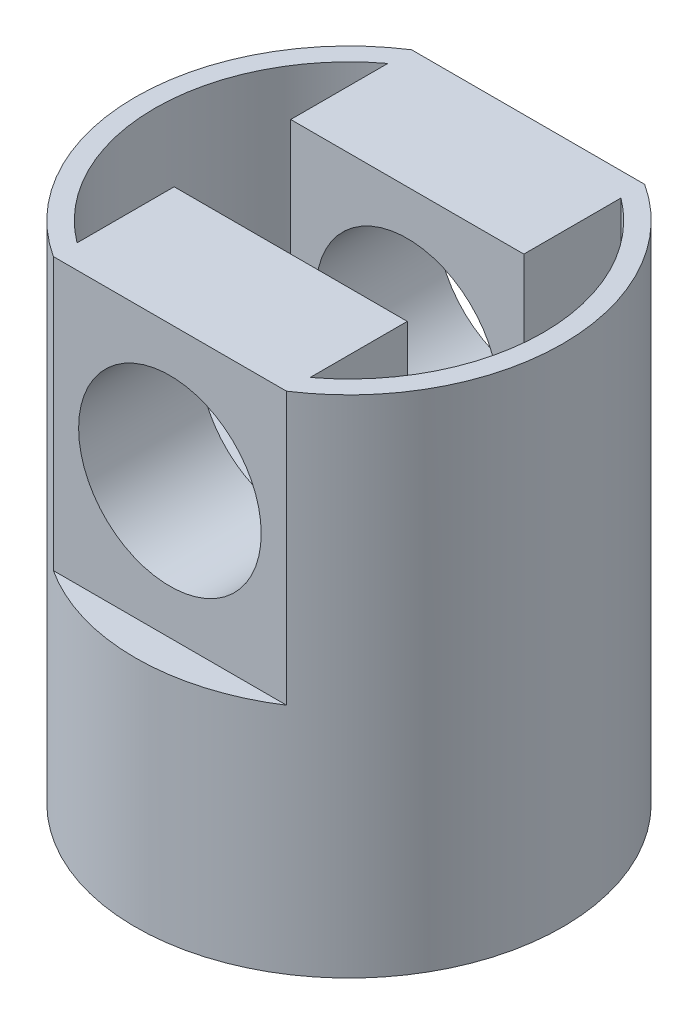
SolidWorks part; units mm, degrees
ref_plane "Front Plane" through (0, 0, 0) normal (0, 0, 1) x (1, 0, 0)
ref_plane "Top Plane" through (0, 0, 0) normal (0, 1, 0) x (1, 0, 0)
ref_plane "Right Plane" through (0, 0, 0) normal (1, 0, 0) x (0, 0, -1)
sketch "Sketch1" plane through (0, 0, 0) normal (0, 0, 1) x (1, 0, 0)
  line L0 (0, 0) -> (0, 2)
  line L1 (-10, 16) -> (-11, 16)
  line L2 (-11, 16) -> (-11, -10)
  line L3 (-11, -10) -> (-10, -10)
  line L4 (-10, -10) -> (-10, 0)
  line L5 (-10, 0) -> (0, 0)
  line L6 (-10, 16) -> (-10, 2)
  line L7 (-10, 2) -> (0, 2)
  dimension "D1" = 1
  dimension "D2" = 26
  dimension "D3" = 1
  dimension "D4" = 10
  dimension "D5" = 14
  dimension "D6" = 10
revolve "Revolve1" add sketch "Sketch1" angle 360 about L0
sketch "Sketch2" plane through (0, -10, 0) normal (0, -1, 0) x (1, 0, 0)
  line L0 (-11, 0) -> (11, 0) construction
  line L2 (-11.5, -2) -> (-8.5, -2)
  line L3 (-11.5, -2) -> (-11.5, 2)
  line L4 (-11.5, 2) -> (-8.5, 2)
  line L5 (-8.5, -2) -> (-8.5, 2)
  line L6 (-11.5, -2) -> (-8.5, 2) construction
  line L7 (-11.5, 2) -> (-8.5, -2) construction
  circle A0 centre (0, 0) radius 11 construction
  circle A2 centre (0, 0) radius 10 construction
  point P7 (-10, 0)
  point P10 (-10, 0)
  dimension "D1" = 3
  dimension "D2" = 4
extrude "Cut-Extrude2" cut sketch "Sketch2" against normal up to surface (10 mm away) up to face at (0, 0, -10)
sketch "Sketch6" plane through (0, 16, 0) normal (0, 1, 0) x (1, 0, 0)
  line L0 (0, -11) -> (0, 11) construction
  line L2 (-6, -17) -> (6, -17)
  line L3 (-6, -17) -> (-6, -3)
  line L4 (-6, -3) -> (6, -3)
  line L5 (6, -17) -> (6, -3)
  line L6 (-6, -17) -> (6, -3) construction
  line L7 (-6, -3) -> (6, -17) construction
  line L8 (-6, 3) -> (6, 3)
  line L9 (-6, 3) -> (-6, 17)
  line L10 (-6, 17) -> (6, 17)
  line L11 (6, 3) -> (6, 17)
  line L12 (-6, 3) -> (6, 17) construction
  line L13 (-6, 17) -> (6, 3) construction
  circle A0 centre (0, 0) radius 11 construction
  circle A1 centre (0, 0) radius 10 construction
  circle A2 centre (0, 0) radius 10 construction
  point P5 (0, -10)
  point P12 (0, 10)
  dimension "D1" = 12
  dimension "D2" = 3
  dimension "D3" = 3
  dimension "D4" = 12
extrude "Cut-Extrude3" cut sketch "Sketch6" against normal up to surface (14 mm away) up to face at (0, 2, -10)
sketch "Sketch7" plane through (0, 16, 0) normal (0, 1, 0) x (1, 0, 0)
  line L0 (-6, 9.2195) -> (6, 9.2195)
  line L1 (6, 9.2195) -> (6, 3)
  line L2 (6, 3) -> (-6, 3)
  line L3 (-6, 3) -> (-6, 9.2195)
  line L4 (-6, -3) -> (-6, -9.2195)
  line L5 (-6, -9.2195) -> (6, -9.2195)
  line L6 (6, -9.2195) -> (6, -3)
  line L7 (6, -3) -> (-6, -3)
  line L8 (-10, 0) -> (10, 0) construction
  arc A0 (-6, 8) -> (-6, -8) centre (0, 0) ccw construction
  arc A1 (6, -8) -> (6, 8) centre (0, 0) ccw construction
  dimension "D1" = 3
  dimension "D2" = 3
extrude "Boss-Extrude1" add sketch "Sketch7" against normal up to surface (14 mm away)
sketch "Sketch8" plane through (0, 0, 9.2195) normal (0, 0, 1) x (1, 0, 0)
  line L0 (0, 16) -> (0, 2) construction
  line L1 (-6, 16) -> (6, 16) construction
  line L2 (-6, 2) -> (6, 2) construction
  circle A0 centre (0, 9) radius 4.7
  dimension "D1" = 9.4
extrude "Cut-Extrude4" cut sketch "Sketch8" against normal up to surface (18.4391 mm away) up to face at (0, 9, -9.2195)
